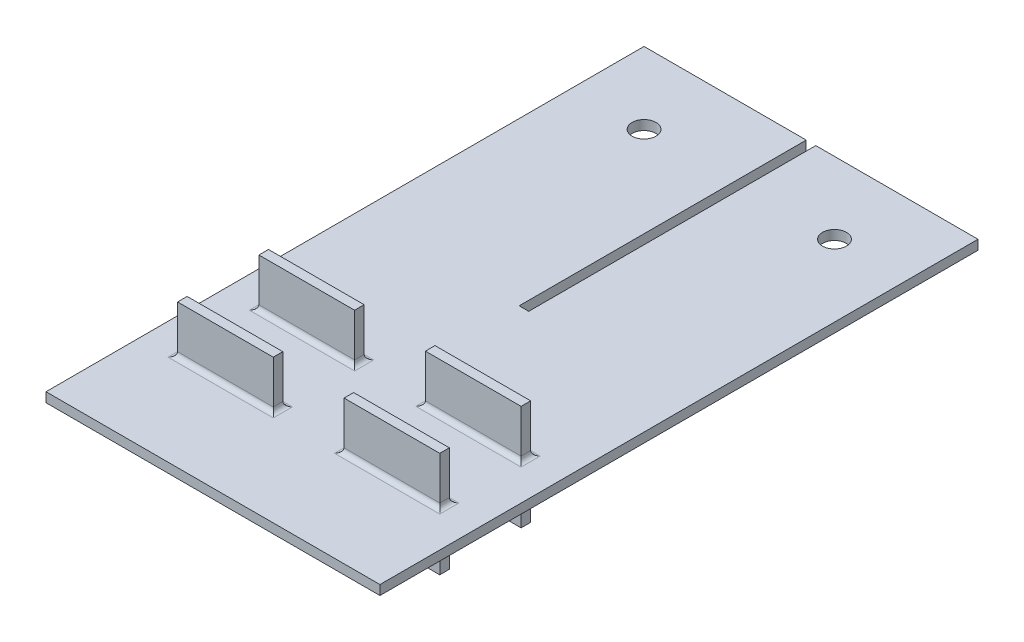
SolidWorks part; units mm, degrees
ref_plane "Front Plane" through (0, 0, 0) normal (0, 0, 1) x (1, 0, 0)
ref_plane "Top Plane" through (0, 0, 0) normal (0, 1, 0) x (1, 0, 0)
ref_plane "Right Plane" through (0, 0, 0) normal (1, 0, 0) x (0, 0, -1)
sketch "Sketch1" plane through (0, 0, 0) normal (0, 1, 0) x (1, 0, 0)
  line L0 (1, 62.5) -> (34.9, 62.5)
  line L1 (-34.9, 62.5) -> (-1, 62.5)
  line L2 (-34.9, 62.5) -> (-34.9, -62.5)
  line L3 (-34.9, -62.5) -> (34.9, -62.5)
  line L4 (34.9, 62.5) -> (34.9, -62.5)
  line L5 (-34.9, 62.5) -> (34.9, -62.5) construction
  line L6 (-34.9, -62.5) -> (34.9, 62.5) construction
  line L7 (1, 2.5) -> (-1, 2.5)
  line L8 (1, 2.5) -> (1, 62.5)
  line L10 (-1, 2.5) -> (-1, 62.5)
  line L11 (1, 2.5) -> (-1, 62.5) construction
  line L12 (1, 62.5) -> (-1, 2.5) construction
  line L13 (0, 32.5) -> (0, -55) construction
  circle A2 centre (-19.9, 47.5) radius 2.5
  circle A3 centre (19.9, 47.5) radius 2.5
  point P0 (0, 0)
  point P6 (0, 32.5)
  dimension "D6" = 15
  dimension "D8" = 5
  dimension "D9" = 5
  dimension "D1" = 69.8
  dimension "D2" = 125
  dimension "D3" = 2
  dimension "D4" = 33.9
  dimension "D5" = 60
  dimension "D7" = 15
  dimension "D10" = 15
  dimension "D11" = 15
extrude "Boss-Extrude1" add sketch "Sketch1" along normal mid plane 2
sketch "Sketch2" plane through (0, 1, 0) normal (0, 1, 0) x (1, 0, 0)
  line L0 (0, 0) -> (0, -13.0633) construction
  line L1 (-34.9, -62.5) -> (34.9, -62.5) construction
  line L2 (7.4, -23.5) -> (27.4, -23.5)
  line L3 (7.4, -23.5) -> (7.4, -25.5)
  line L4 (7.4, -25.5) -> (27.4, -25.5)
  line L5 (27.4, -23.5) -> (27.4, -25.5)
  line L6 (7.4, -40.5) -> (27.4, -40.5)
  line L7 (7.4, -40.5) -> (7.4, -42.5)
  line L8 (7.4, -42.5) -> (27.4, -42.5)
  line L9 (27.4, -40.5) -> (27.4, -42.5)
  line L10 (34.9, -62.5) -> (34.9, 62.5) construction
  line L11 (-7.4, -42.5) -> (-27.4, -42.5)
  line L12 (-7.4, -40.5) -> (-27.4, -40.5)
  line L13 (-7.4, -40.5) -> (-7.4, -42.5)
  line L14 (-7.4, -23.5) -> (-7.4, -25.5)
  line L15 (-27.4, -23.5) -> (-27.4, -25.5)
  line L16 (-7.4, -25.5) -> (-27.4, -25.5)
  line L17 (-7.4, -23.5) -> (-27.4, -23.5)
  line L18 (-27.4, -40.5) -> (-27.4, -42.5)
  point P17 (-27.4, -40.5)
  dimension "D1" = 20
  dimension "D2" = 2
  dimension "D3" = 20
  dimension "D4" = 7.5
  dimension "D5" = 15
  dimension "D6" = 2
  dimension "D7" = 7.5
  dimension "D8" = 20
extrude "Boss-Extrude2" add sketch "Sketch2" along normal blind 10
mirror "Mirror1" about plane through (0, 0, 0) normal (0, 1, 0) of "Boss-Extrude2", "Boss-Extrude1"
fillet "Fillet2" radius 1 16 edges at (27.4, -1, 41.5) (17.4, -1, 40.5) (7.4, -1, 41.5) (17.4, -1, 42.5) (-27.4, -1, 41.5) (-17.4, -1, 42.5) (-7.4, -1, 41.5) (-17.4, -1, 40.5) (-17.4, -1, 23.5) (-7.4, -1, 24.5) (-17.4, -1, 25.5) (-27.4, -1, 24.5) (27.4, -1, 24.5) (17.4, -1, 25.5) (7.4, -1, 24.5) (17.4, -1, 23.5)
fillet "Fillet3" radius 1 16 edges at (-7.4, 1, 41.5) (-17.4, 1, 40.5) (-27.4, 1, 41.5) (-17.4, 1, 42.5) (17.4, 1, 42.5) (7.4, 1, 41.5) (27.4, 1, 41.5) (17.4, 1, 40.5) (-7.4, 1, 24.5) (-17.4, 1, 23.5) (-27.4, 1, 24.5) (-17.4, 1, 25.5) (7.4, 1, 24.5) (17.4, 1, 25.5) (27.4, 1, 24.5) (17.4, 1, 23.5)
